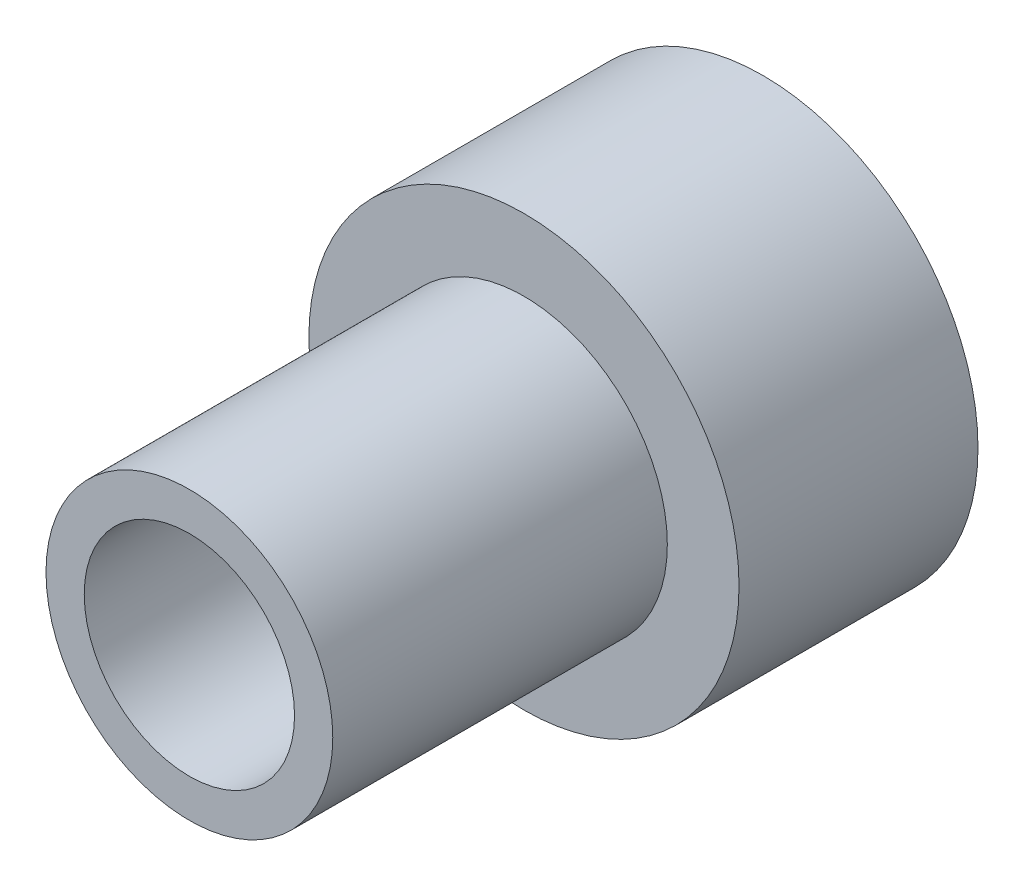
SolidWorks part; units mm, degrees
ref_plane "Front Plane" through (0, 0, 0) normal (0, 0, 1) x (1, 0, 0)
ref_plane "Top Plane" through (0, 0, 0) normal (0, 1, 0) x (1, 0, 0)
ref_plane "Right Plane" through (0, 0, 0) normal (1, 0, 0) x (0, 0, -1)
sketch "Sketch1" plane through (0, 0, 0) normal (0, 1, 0) x (1, 0, 0)
  line L0 (0, 0) -> (0, 6.3181) construction
  line L1 (-1.1, 0) -> (-1.5, 0)
  line L2 (-1.5, 0) -> (-1.5, 3.5)
  line L3 (-1.5, 3.5) -> (-2.25, 3.5)
  line L4 (-2.25, 3.5) -> (-2.25, 6)
  line L5 (-2.25, 6) -> (-1.9, 6)
  line L6 (-1.9, 6) -> (-1.9, 4.5)
  line L7 (-1.9, 4.5) -> (-1.1, 4.5)
  line L8 (-1.1, 4.5) -> (-1.1, 0)
  point P11 (0, 0)
  dimension "D1" = 2.2
  dimension "D2" = 3
  dimension "D3" = 4.5
  dimension "D4" = 3.8
  dimension "D5" = 3.5
  dimension "D6" = 1
  dimension "D7" = 1.5
revolve "Revolve1" add sketch "Sketch1" angle 360 about L0
